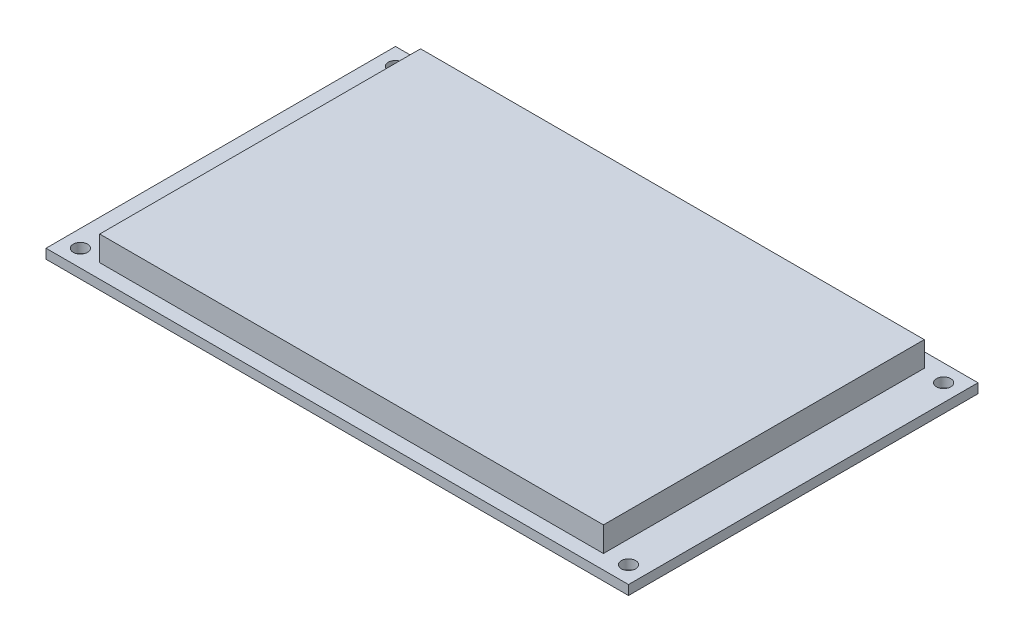
SolidWorks part; units mm, degrees
material "AISI 304"
ref_plane "前视基准面" through (0, 0, 0) normal (0, 0, 1) x (1, 0, 0)
ref_plane "上视基准面" through (0, 0, 0) normal (0, 1, 0) x (1, 0, 0)
ref_plane "右视基准面" through (0, 0, 0) normal (1, 0, 0) x (0, 0, -1)
other "Configuration Table"
sketch "草图1" plane through (0, 0, 0) normal (0, 1, 0) x (1, 0, 0)
  line L0 (0, 0) -> (0, 48.5103) construction
  line L1 (-61, -36.6) -> (61, -36.6)
  line L2 (-61, -36.6) -> (-61, 36.6)
  line L3 (-61, 36.6) -> (61, 36.6)
  line L4 (61, -36.6) -> (61, 36.6)
  line L5 (-61, -36.6) -> (61, 36.6) construction
  line L6 (-61, 36.6) -> (61, -36.6) construction
  line L7 (0, 0) -> (77.1287, 0) construction
  circle A0 centre (57.4, 33) radius 1.5
  circle A1 centre (57.4, -33) radius 1.5
  circle A2 centre (-57.4, -33) radius 1.5
  circle A3 centre (-57.4, 33) radius 1.5
  point P0 (0, 0)
  dimension "D3" = 3
  dimension "D4" = 114.8
  dimension "D5" = 66
  dimension "D1" = 122
  dimension "D2" = 73.2
extrude "凸台-拉伸1" add sketch "草图1" along normal blind 2
sketch "草图2" plane through (0, 2, 0) normal (0, 1, 0) x (1, 0, 0)
  line L1 (-52.75, -33.6) -> (52.75, -33.6)
  line L2 (-52.75, -33.6) -> (-52.75, 33.6)
  line L3 (-52.75, 33.6) -> (52.75, 33.6)
  line L4 (52.75, -33.6) -> (52.75, 33.6)
  line L5 (-52.75, -33.6) -> (52.75, 33.6) construction
  line L6 (-52.75, 33.6) -> (52.75, -33.6) construction
  point P0 (0, 0)
  dimension "D1" = 105.5
  dimension "D2" = 67.2
extrude "凸台-拉伸2" add sketch "草图2" along normal blind 5.2
